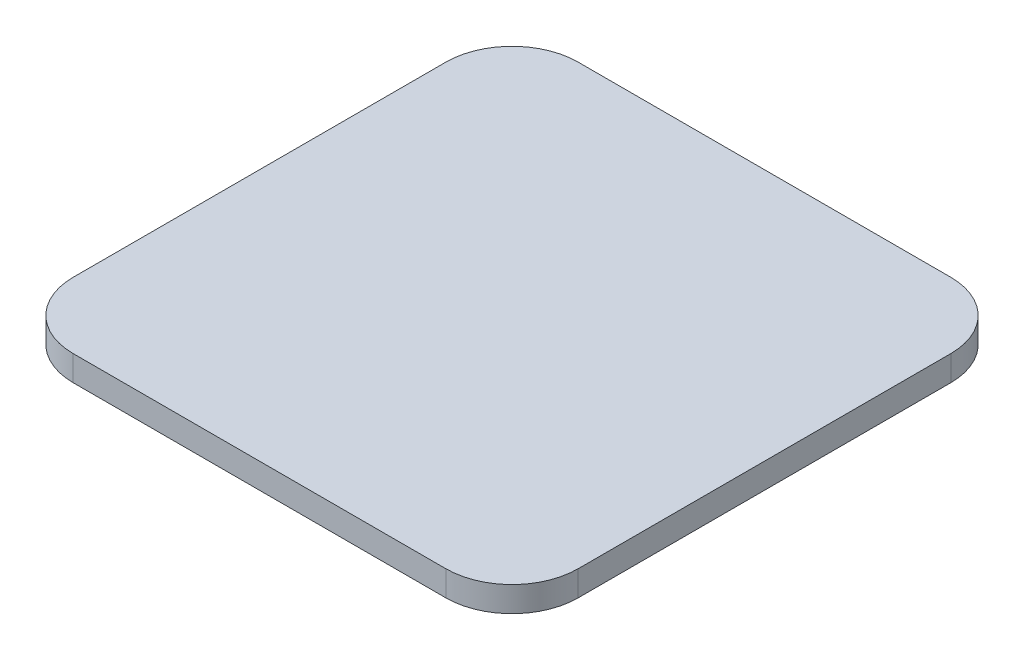
SolidWorks part; units mm, degrees
ref_plane "Front Plane" through (0, 0, 0) normal (0, 0, 1) x (1, 0, 0)
ref_plane "Top Plane" through (0, 0, 0) normal (0, 1, 0) x (1, 0, 0)
ref_plane "Right Plane" through (0, 0, 0) normal (1, 0, 0) x (0, 0, -1)
sketch "Sketch1" plane through (0, 0, 0) normal (0, 1, 0) x (1, 0, 0)
  line L1 (-37.4951, 50.8) -> (37.4951, 50.8)
  line L2 (-50.8, 37.4951) -> (-50.8, -37.4951)
  line L3 (-37.4951, -50.8) -> (37.4951, -50.8)
  line L4 (50.8, 37.4951) -> (50.8, -37.4951)
  line L5 (-50.8, 50.8) -> (50.8, -50.8) construction
  line L6 (-50.8, -50.8) -> (50.8, 50.8) construction
  arc A0 (37.4951, -50.8) -> (50.8, -37.4951) centre (37.4951, -37.4951) ccw
  arc A1 (37.4951, 50.8) -> (50.8, 37.4951) centre (37.4951, 37.4951) cw
  arc A2 (-37.4951, 50.8) -> (-50.8, 37.4951) centre (-37.4951, 37.4951) ccw
  arc A3 (-50.8, -37.4951) -> (-37.4951, -50.8) centre (-37.4951, -37.4951) ccw
  point P0 (0, 0)
  dimension "D3" = 13.3049
  dimension "D1" = 101.6
  dimension "D2" = 101.6
extrude "Boss-Extrude1" add sketch "Sketch1" along normal blind 5.08
sketch "Sketch2" plane through (0, 0, 0) normal (0, -1, 0) x (1, 0, 0)
  circle A0 centre (0, 0) radius 38.1
  dimension "D1" = 76.2
extrude "Boss-Extrude2" add sketch "Sketch2" along normal blind 10.16
sketch "Sketch3" plane through (0, 0, 0) normal (1, 0, 0) x (0, 0, -1)
  line L0 (-38.1, 0) -> (-38.1, -10.16) construction
  line L1 (0, 0) -> (0, -14.9636) construction
  line L2 (-37.4951, 0) -> (37.4951, 0) construction
  circle A0 centre (-38.1, -7.62) radius 2.54
  dimension "D1" = 5.08
revolve "Revolve1" add sketch "Sketch3" angle 360 about L1
sketch "Sketch5" plane through (0, -10.16, 0) normal (0, -1, 0) x (1, 0, 0)
  circle A0 centre (0, 0) radius 7.62
  dimension "D1" = 15.24
extrude "Boss-Extrude3" add sketch "Sketch5" along normal blind 27.94
cosmetic thread "Cosmetic Thread1" parameters "D2"=11.7678
chamfer "Chamfer4" distance 0.9906 angle 45 1 edges at (0, -38.1, -7.62)
